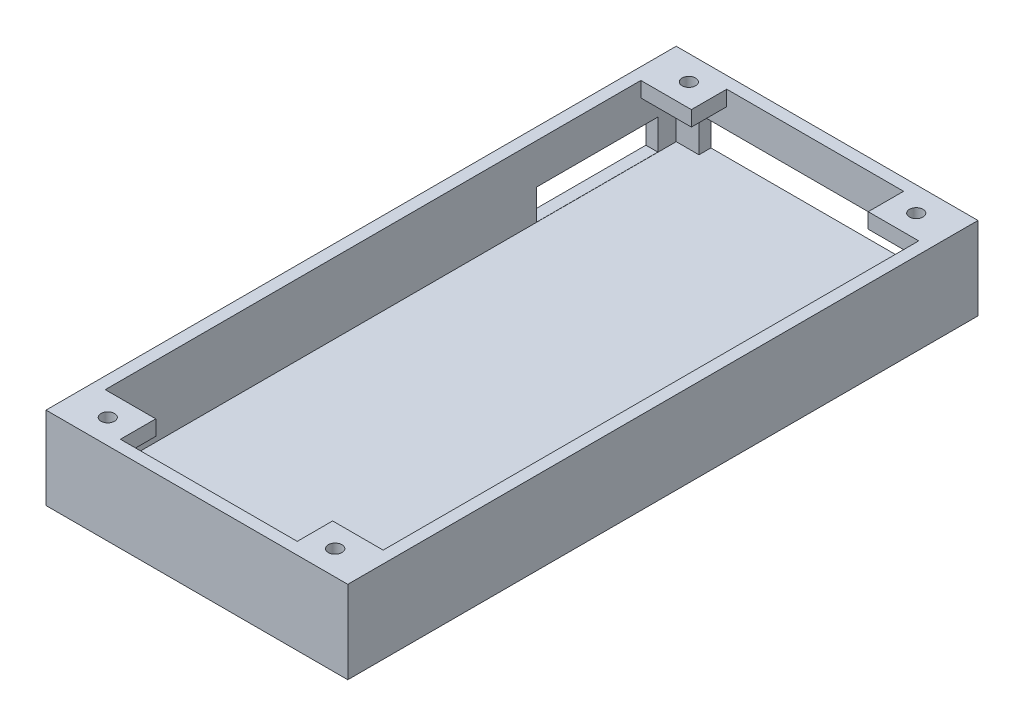
SolidWorks part; units mm, degrees
material "1060 Alloy"
ref_plane "Front Plane" through (0, 0, 0) normal (0, 0, 1) x (1, 0, 0)
ref_plane "Top Plane" through (0, 0, 0) normal (0, 1, 0) x (1, 0, 0)
ref_plane "Right Plane" through (0, 0, 0) normal (1, 0, 0) x (0, 0, -1)
sketch "Sketch1" plane through (0, 0, 0) normal (0, 1, 0) x (1, 0, 0)
  line L0 (-37.925, 79.2) -> (37.925, 79.2)
  line L1 (-34.925, 76.2) -> (34.925, 76.2)
  line L2 (-34.925, 76.2) -> (-34.925, -76.2)
  line L3 (-34.925, -76.2) -> (34.925, -76.2)
  line L4 (34.925, 76.2) -> (34.925, -76.2)
  line L5 (-34.925, 76.2) -> (34.925, -76.2) construction
  line L6 (-34.925, -76.2) -> (34.925, 76.2) construction
  line L7 (37.925, 79.2) -> (37.925, -79.2)
  line L8 (-37.925, -79.2) -> (37.925, -79.2)
  line L9 (-37.925, 79.2) -> (-37.925, -79.2)
  point P0 (0, 0)
  dimension "D1" = 69.85
  dimension "D2" = 152.4
  dimension "D3" = 3
extrude "Boss-Extrude1" add sketch "Sketch1" along normal blind 3 contours L9 L8 L7 L0
sketch "Sketch2" plane through (0, 3, 0) normal (0, 1, 0) x (1, 0, 0)
  line L1 (-37.925, 79.2) -> (37.925, 79.2)
  line L2 (-37.925, 79.2) -> (-37.925, -79.2)
  line L3 (-37.925, -79.2) -> (37.925, -79.2)
  line L4 (37.925, 79.2) -> (37.925, -79.2)
  line L5 (-37.925, 79.2) -> (37.925, -79.2) construction
  line L6 (-37.925, -79.2) -> (37.925, 79.2) construction
  line L7 (-34.925, 76.2) -> (34.925, 76.2)
  line L8 (-34.925, 76.2) -> (-34.925, -76.2)
  line L9 (-34.925, -76.2) -> (34.925, -76.2)
  line L10 (34.925, 76.2) -> (34.925, -76.2)
  line L11 (-34.925, 76.2) -> (34.925, -76.2) construction
  line L12 (-34.925, -76.2) -> (34.925, 76.2) construction
  point P0 (0, 0)
  point P7 (0, 0)
  dimension "D1" = 152.4
  dimension "D2" = 69.85
extrude "Boss-Extrude2" add sketch "Sketch2" along normal blind 17.78
sketch "Sketch3" plane through (0, 20.78, 0) normal (0, 1, 0) x (1, 0, 0)
  line L1 (-34.925, 76.2) -> (-22.225, 76.2)
  line L2 (-34.925, 76.2) -> (-34.925, 67.31)
  line L3 (-34.925, 67.31) -> (-22.225, 67.31)
  line L4 (-22.225, 76.2) -> (-22.225, 67.31)
  line L5 (-34.925, -76.2) -> (-22.225, -76.2)
  line L6 (-34.925, -76.2) -> (-34.925, -67.31)
  line L7 (-34.925, -67.31) -> (-22.225, -67.31)
  line L8 (-22.225, -76.2) -> (-22.225, -67.31)
  line L9 (34.925, 76.2) -> (22.225, 76.2)
  line L10 (34.925, 76.2) -> (34.925, 67.31)
  line L11 (34.925, 67.31) -> (22.225, 67.31)
  line L12 (22.225, 76.2) -> (22.225, 67.31)
  line L13 (34.925, -76.2) -> (22.225, -76.2)
  line L14 (34.925, -76.2) -> (34.925, -67.31)
  line L15 (34.925, -67.31) -> (22.225, -67.31)
  line L16 (22.225, -76.2) -> (22.225, -67.31)
  point P20 (-28.575, 70.485)
  point P21 (-28.575, -73.025)
  point P22 (28.575, -73.025)
  point P23 (28.575, 73.025)
  dimension "D1" = 12.7
  dimension "D2" = 8.89
  dimension "D3" = 8.89
  dimension "D4" = 12.7
  dimension "D5" = 12.7
  dimension "D6" = 8.89
  dimension "D7" = 8.89
  dimension "D8" = 12.7
  dimension "D9" = 6.35
  dimension "D10" = 3.175
  dimension "D11" = 6.35
  dimension "D12" = 3.175
  dimension "D13" = 6.35
  dimension "D14" = 3.175
  dimension "D15" = 6.35
  dimension "D16" = 3.175
extrude "Boss-Extrude3" add sketch "Sketch3" against normal blind 3.81
sketch "Sketch4" plane through (0, 20.78, 0) normal (0, 1, 0) x (1, 0, 0)
  line L0 (-22.225, 67.31) -> (-22.225, 76.2) construction
  line L3 (-22.225, -76.2) -> (-22.225, -67.31) construction
  line L4 (22.225, -67.31) -> (22.225, -76.2) construction
  line L7 (22.225, 76.2) -> (22.225, 67.31) construction
  line L9 (22.225, 76.2) -> (-22.225, 76.2) construction
  line L10 (-34.925, -76.2) -> (34.925, -76.2) construction
  line L11 (34.925, 76.2) -> (-34.925, 76.2) construction
  line L12 (-22.225, -76.2) -> (22.225, -76.2) construction
  circle A0 centre (-28.575, 73.025) radius 1.7
  circle A1 centre (28.575, 73.025) radius 1.7
  circle A2 centre (28.575, -73.025) radius 1.72
  circle A3 centre (-28.575, -73.025) radius 1.7
  point P0 (-28.575, 73.025)
  point P1 (-28.575, -73.025)
  point P2 (28.575, -73.025)
  point P3 (28.575, 73.025)
  dimension "D9" = 3.4
  dimension "D10" = 3.4
  dimension "D11" = 3.4
  dimension "D12" = 3.44
  dimension "D1" = 6.35
  dimension "D2" = 3.175
  dimension "D3" = 3.175
  dimension "D4" = 6.35
  dimension "D5" = 6.35
  dimension "D6" = 3.175
  dimension "D7" = 3.175
  dimension "D8" = 6.35
sketch "Sketch6" plane through (37.925, 0, 0) normal (1, 0, 0) x (0, 0, -1)
  line L1 (-12.7, 3) -> (12.7, 3)
  line L2 (-12.7, 3) -> (-12.7, 10.62)
  line L3 (-12.7, 10.62) -> (12.7, 10.62)
  line L4 (12.7, 3) -> (12.7, 10.62)
  line L6 (79.2, 0) -> (-79.2, 0) construction
  point P6 (0, 3)
  dimension "D1" = 7.62
  dimension "D2" = 3
  dimension "D3" = 25.4
sketch "Sketch7" plane through (0, 0, 0) normal (0, -1, 0) x (1, 0, 0)
  line L1 (-25.4, 21.35) -> (25.4, 21.35)
  line L2 (-25.4, 21.35) -> (-25.4, -21.35)
  line L3 (-25.4, -21.35) -> (25.4, -21.35)
  line L4 (25.4, 21.35) -> (25.4, -21.35)
  line L5 (-25.4, 21.35) -> (25.4, -21.35) construction
  line L6 (-25.4, -21.35) -> (25.4, 21.35) construction
  point P0 (0, 0)
  dimension "D1" = 42.7
  dimension "D2" = 50.8
extrude "Cut-Extrude4" cut sketch "Sketch4" against normal up to next contours A1 | A2 | A3 | A0
sketch "Sketch10" plane through (0, 0, -79.2) normal (0, 0, -1) x (-1, 0, 0)
  line L0 (37.925, 0) -> (-37.925, 0) construction
  line L1 (-29.21, 3) -> (29.21, 3)
  line L2 (-29.21, 3) -> (-29.21, 11.89)
  line L3 (-29.21, 11.89) -> (29.21, 11.89)
  line L4 (29.21, 3) -> (29.21, 11.89)
  point P6 (0, 3)
  dimension "D1" = 3
  dimension "D2" = 8.89
  dimension "D3" = 58.42
extrude "Cut-Extrude5" cut sketch "Sketch10" against normal up to next
sketch "Sketch11" plane through (-37.925, 0, 0) normal (-1, 0, 0) x (0, 0, 1)
  line L0 (-79.2, 0) -> (79.2, 0) construction
  line L1 (-71.58, 3.048) -> (-41.1, 3.048)
  line L2 (-71.58, 3.048) -> (-71.58, 10.668)
  line L3 (-71.58, 10.668) -> (-41.1, 10.668)
  line L4 (-41.1, 3.048) -> (-41.1, 10.668)
  line L5 (-79.2, 20.78) -> (-79.2, 0) construction
  dimension "D1" = 3.048
  dimension "D2" = 7.62
  dimension "D3" = 38.1
  dimension "D4" = 7.62
extrude "Cut-Extrude6" cut sketch "Sketch11" against normal up to next
sketch "Sketch12" plane through (0, 0, 0) normal (0, -1, 0) x (1, 0, 0)
  line L0 (-8.89, 10.16) -> (8.89, 10.16)
  line L1 (-8.89, 15.24) -> (8.89, 15.24)
  line L2 (-8.89, 15.24) -> (-8.89, -15.24)
  line L3 (-8.89, -15.24) -> (8.89, -15.24)
  line L4 (8.89, 15.24) -> (8.89, -15.24)
  line L5 (-8.89, 15.24) -> (8.89, -15.24) construction
  line L6 (-8.89, -15.24) -> (8.89, 15.24) construction
  line L7 (-8.89, -10.16) -> (8.89, -10.16)
  point P0 (0, 0)
  dimension "D1" = 17.78
  dimension "D2" = 30.48
  dimension "D3" = 5.08
  dimension "D4" = 5.08
extrude "Boss-Extrude4" add sketch "Sketch12" along normal blind 5.08 contours L4 L1 L2 L0 | L7 L2 L3 L4
sketch "Sketch13" plane through (0, 0, 10.16) normal (0, 0, -1) x (-1, 0, 0)
  line L0 (8.89, -5.08) -> (8.89, 0) construction
  line L1 (-8.89, -5.08) -> (8.89, -5.08)
  line L2 (-8.89, -5.08) -> (-8.89, -2.54)
  line L3 (-8.89, -2.54) -> (8.89, -2.54)
  line L4 (8.89, -5.08) -> (8.89, -2.54)
  dimension "D1" = 2.54
extrude "Boss-Extrude5" add sketch "Sketch13" along normal blind 5.08
ref_plane "Plane1" through (0, 0, 0) normal (0, 0, -1) x (-1, 0, 0)
mirror "Mirror1" about plane through (0, 0, 0) normal (0, 0, -1) of "Boss-Extrude5"
